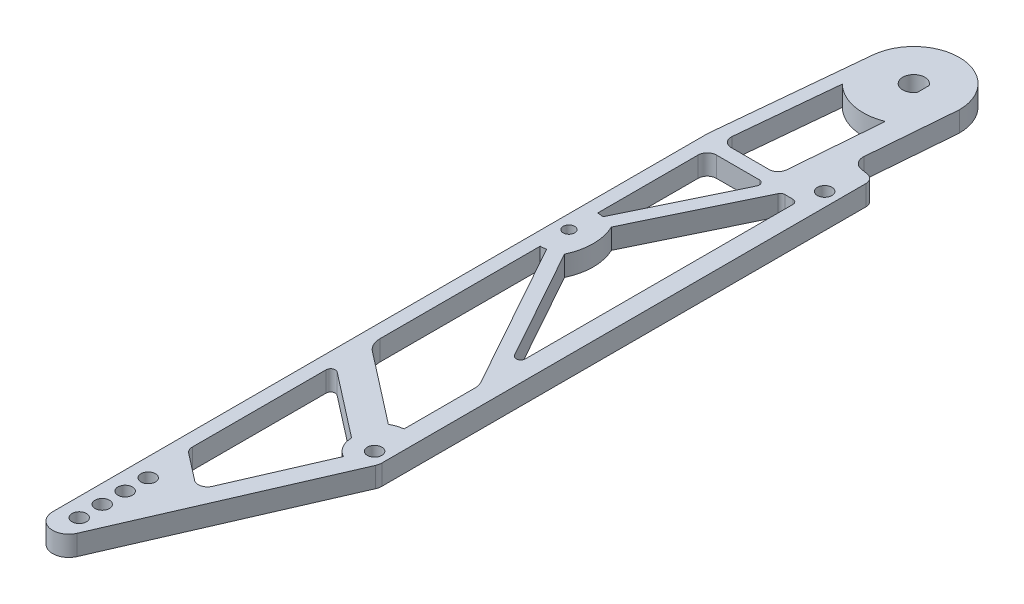
SolidWorks part; units mm, degrees
material "6061-T6 (SS)"
ref_plane "X-Y Datum" through (0, 0, 0) normal (0, 0, 1) x (1, 0, 0)
ref_plane "X-Z Datum" through (0, 0, 0) normal (0, 1, 0) x (1, 0, 0)
ref_plane "Y-Z Datum" through (0, 0, 0) normal (1, 0, 0) x (0, 0, -1)
other "Graphic1" [suppressed]
other "Graphic (Closed) -1" [suppressed]
sketch "Sketch2" plane through (0, 0, 0) normal (0, 1, 0) x (1, 0, 0)
  line L5 (13.4859, -162.4108) -> (-11.43, -143.082) construction
  line L8 (0, 0) -> (0, -24.13) construction
  line L11 (15.1556, -28.0184) -> (13.2387, -27.713)
  line L15 (-16.51, -221.3289) -> (-16.51, -40.4661)
  line L22 (-7.9887, -223.1013) -> (16.9799, -165.6775)
  line L23 (17.2959, -164.1583) -> (17.2959, -30.5268)
  line L33 (10.4385, -167.9818) -> (-0.5342, -193.2173)
  line L44 (-7.4473, -76.0744) -> (7.5755, -45.0536)
  line L45 (8.7185, -44.3372) -> (10.9459, -44.3372)
  line L46 (12.2159, -45.6072) -> (12.2159, -119.4928)
  line L47 (9.8359, -120.11) -> (-7.4473, -89.0256)
  line L49 (-12.4315, -37.7433) -> (-9.7554, -9.9996)
  line L51 (5.1277, -12.9949) -> (3.0693, -38.194)
  line L53 (0.5377, -40.5272) -> (-9.9032, -40.5272)
  line L56 (1.663, -44.3372) -> (-10.16, -44.3372)
  line L57 (13.7382, -24.5776) -> (0, 0) construction
  line L58 (10.5738, -24.3191) -> (12.5603, 0)
  line L59 (-12.7, -149.6154) -> (-12.7, -186.5441)
  line L63 (7.1359, -162.4108) -> (-10.6516, -148.612)
  line L64 (-12.7, -74.6125) -> (-12.7, -46.8772)
  line L65 (2.8061, -46.1607) -> (-11.056, -74.7846)
  line L66 (-16.4983, -40.2222) -> (-12.5023, 1.2059)
  line L67 (-4.4204, -194.2114) -> (-11.7169, -188.551)
  line L68 (5.8058, -44.3372) -> (-12.7, -82.55) construction
  line L69 (-1.7326, -64.2739) -> (-5.1616, -62.6133) construction
  line L70 (8.9236, -154.0495) -> (-10.7338, -138.8001)
  line L71 (12.2159, -152.9708) -> (12.2159, -133.548)
  line L72 (11.5758, -131.0794) -> (-11.086, -90.3217)
  line L75 (-12.7, -134.7862) -> (-12.7, -90.4875)
  line L76 (2.6, -1.5945) -> (2.6, 1.5945)
  circle A0 centre (0, 0) radius 3.05
  circle A2 centre (-11.43, -219.075) radius 2
  circle A3 centre (-11.43, -212.725) radius 2
  circle A4 centre (-11.43, -206.375) radius 2
  circle A5 centre (-11.43, -200.025) radius 2
  circle A7 centre (0, 0) radius 12.5603 construction
  circle A8 centre (-12.7, -82.55) radius 1.5875
  circle A12 centre (13.4859, -38.1) radius 2
  arc A13 (-12.5023, 1.2059) -> (12.5603, 0) centre (0, 0) cw
  arc A14 (-7.4473, -89.0256) -> (-7.4473, -76.0744) centre (-20.962, -82.55) ccw
  circle A16 centre (24.0125, -14.7036) radius 3.175 construction
  arc A17 (24.0125, -14.7036) -> (13.7382, -24.5776) centre (0, 0) cw construction
  circle A18 centre (13.7382, -24.5776) radius 3.175 construction
  arc A19 (13.2387, -27.713) -> (10.5738, -24.3191) centre (13.7382, -24.5776) cw
  arc A20 (15.1556, -28.0184) -> (17.2959, -30.5268) centre (14.7559, -30.5268) cw
  circle A21 centre (13.4859, -162.4108) radius 2
  arc A24 (10.4385, -167.9818) -> (7.1359, -162.4108) centre (13.4859, -162.4108) cw
  arc A25 (-16.51, -221.3289) -> (-7.9887, -223.1013) centre (-12.065, -221.3289) ccw
  arc A26 (-12.7, -74.6125) -> (-11.056, -74.7846) centre (-12.7, -82.55) cw
  arc A28 (5.1277, -12.9949) -> (-9.7554, -9.9996) centre (0, 0) cw
  arc A31 (-10.16, -44.3372) -> (-12.7, -46.8772) centre (-10.16, -46.8772) ccw
  arc A32 (-12.4315, -37.7433) -> (-9.9032, -40.5272) centre (-9.9032, -37.9872) ccw
  arc A33 (0.5377, -40.5272) -> (3.0693, -38.194) centre (0.5377, -37.9872) ccw
  arc A36 (-12.7, -149.6154) -> (-10.6516, -148.612) centre (-11.43, -149.6154) cw
  arc A37 (9.8359, -120.11) -> (12.2159, -119.4928) centre (10.9459, -119.4928) ccw
  arc A38 (7.5755, -45.0536) -> (8.7185, -44.3372) centre (8.7185, -45.6072) cw
  arc A39 (10.9459, -44.3372) -> (12.2159, -45.6072) centre (10.9459, -45.6072) cw
  arc A40 (1.663, -44.3372) -> (2.8061, -46.1607) centre (1.663, -45.6072) cw
  arc A50 (17.2959, -164.1583) -> (16.9799, -165.6775) centre (13.4859, -164.1583) cw
  arc A52 (-16.4983, -40.2222) -> (-16.51, -40.4661) centre (-13.97, -40.4661) ccw
  arc A53 (-12.7, -186.5441) -> (-11.7169, -188.551) centre (-10.16, -186.5441) ccw
  arc A54 (-4.4204, -194.2114) -> (-0.5342, -193.2173) centre (-2.8635, -192.2045) ccw
  arc A55 (12.2159, -152.9708) -> (8.9236, -154.0495) centre (13.4859, -162.4108) ccw
  arc A56 (-11.086, -90.3217) -> (-12.7, -90.4875) centre (-12.7, -82.55) cw
  arc A57 (-12.7, -134.7862) -> (-10.7338, -138.8001) centre (-7.62, -134.7862) ccw
  arc A58 (11.5758, -131.0794) -> (12.2159, -133.548) centre (7.1359, -133.548) cw
  point P30 (17.2959, -28.3595)
  point P44 (-3.4471, -63.4436)
  point P45 (-1.8376, -196.215)
  point P48 (12.2159, -82.55)
  point P75 (-3.05, 0)
  point P76 (0, 0)
  point P88 (-12.7, -44.3372)
  point P91 (-12.7, -40.5272)
  point P104 (12.2159, -124.3904)
  point P107 (7.9224, -44.3372)
  point P110 (12.2159, -44.3372)
  point P120 (17.2959, -164.9508)
  dimension "D1" = 6.1
  dimension "D6" = 4
  dimension "D12" = 24.13
  dimension "D5" = 25.1206
  dimension "D14" = 3.175
  dimension "D19" = 4
  dimension "D20" = 6.35
  dimension "D24" = 3.81
  dimension "D50" = 14.986
  dimension "D51" = 8.262
  dimension "D42" = 3.81
  dimension "D62" = 6.35
  dimension "D63" = 29.204
  dimension "D27" = 2.54
  dimension "D44" = 4
  dimension "D18" = 4.445
  dimension "D34" = 3.81
  dimension "D36" = 6.35
  dimension "D33" = 13.97
  dimension "D38" = 3.81
  dimension "D39" = 8.89
  dimension "D48" = 2.54
  dimension "D49" = 1.27
  dimension "D52" = 3.81
  dimension "D53" = 3.81
  dimension "D54" = 9.525
  dimension "D58" = 2.54
  dimension "D59" = 3.81
  dimension "D64" = 5.65
  dimension "D29" = 7.9375
  dimension "D31" = 3.81
  dimension "D41" = 2.54
  dimension "D55" = 7.9375
  dimension "D57" = 5.08
  dimension "D7" = 6.35
  dimension "D8" = 6.35
  dimension "D9" = 6.35
  dimension "D10" = 5.08
  dimension "D11" = 5.08
  dimension "D13" = 4.1084
  dimension "D15" = 82.55
  dimension "D16" = 12.7
  dimension "D17" = 13.7382
  dimension "D21" = 136.5913
  dimension "D22" = 38.1
  dimension "D23" = 13.4859
  dimension "D25" = 5.08
  dimension "D26" = 3.81
  dimension "D28" = 40.5272
  dimension "D30" = 2.54
  dimension "D32" = 3.81
  dimension "D35" = 3.81
  dimension "D37" = 16.51
  dimension "D40" = 23.5
  dimension "D43" = 200.025
  dimension "D45" = 6.35
  dimension "D46" = 6.35
  dimension "D47" = 4.2935
  dimension "D56" = 3.81
  dimension "D60" = 24.0125
  dimension "D61" = 14.7036
extrude "Boss-Extrude1" add sketch "Sketch2" along normal blind 5.588 contours L66 A52 L15 A25 L22 A50 L23 A20 L11 A19 L58 A13 A54 L67 A53 L59 A36 L63 A24 L33 L56 A40 L65 A26 L64 A31 L45 A39 L46 A37 L47 A14 L44 A38 A0 A2 A3 A4 A5 A8 | L76 A0
sketch "Sketch6" plane through (-16.51, 0, 0) normal (-1, 0, 0) x (0, 0, 1)
  line L0 (183.2289, 5.588) -> (183.2289, 0)
  line L3 (221.3289, 5.588) -> (221.3289, 0) construction
  line L4 (221.3289, 5.588) -> (40.4661, 5.588) construction
  line L5 (221.3289, 0) -> (40.4661, 0) construction
  dimension "D1" = 38.1
split line "Split Line2"
sketch "Sketch7" plane through (0, 0, 0) normal (0, -1, 0) x (1, 0, 0)
  line L0 (0, 0) -> (0, 23.7661) construction
